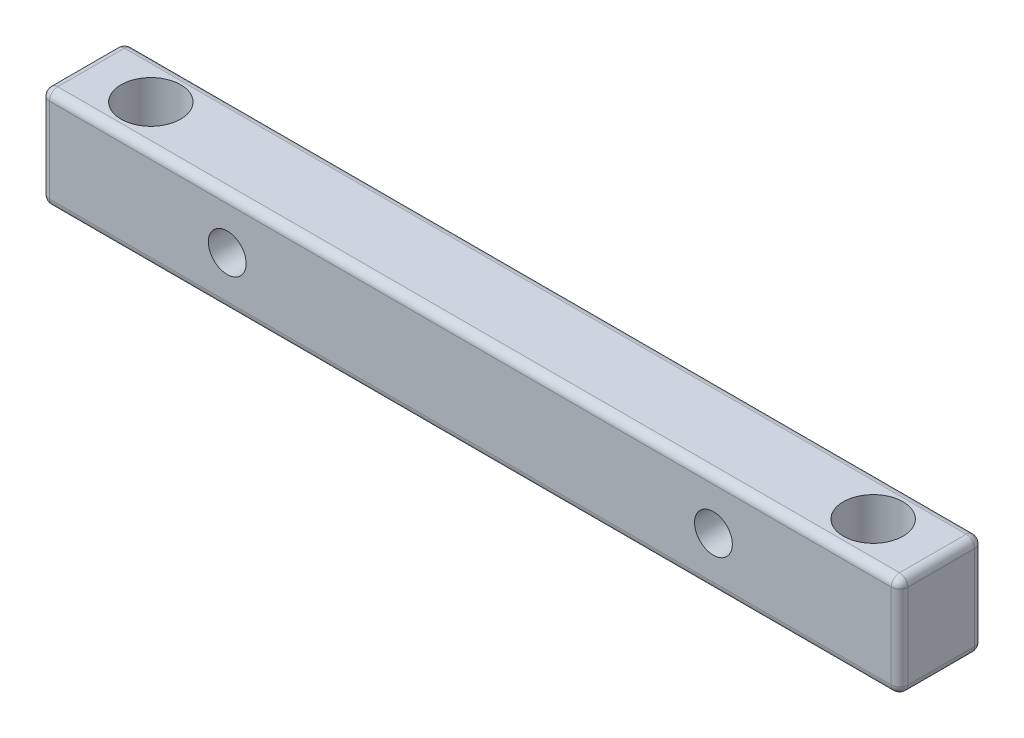
SolidWorks part; units mm, degrees
ref_plane "Front Plane" through (0, 0, 0) normal (0, 0, 1) x (1, 0, 0)
ref_plane "Top Plane" through (0, 0, 0) normal (0, 1, 0) x (1, 0, 0)
ref_plane "Right Plane" through (0, 0, 0) normal (1, 0, 0) x (0, 0, -1)
sketch "Sketch2" plane through (0, 0, 0) normal (0, 1, 0) x (1, 0, 0)
  line L0 (39.243, 7.62) -> (39.243, 0) construction
  line L1 (0, 7.62) -> (78.486, 7.62)
  line L2 (0, 7.62) -> (0, 0)
  line L3 (0, 0) -> (78.486, 0)
  line L4 (78.486, 7.62) -> (78.486, 0)
  line L5 (6.223, 3.81) -> (72.263, 3.81) construction
  circle A0 centre (6.223, 3.81) radius 2.7305
  circle A1 centre (72.263, 3.81) radius 2.7305
  point P10 (39.243, 3.81)
  dimension "D4" = 5.461
  dimension "D1" = 7.62
  dimension "D2" = 78.486
  dimension "D3" = 66.04
extrude "Boss-Extrude1" add sketch "Sketch2" along normal blind 9.271
sketch "Sketch3" plane through (0, 0, 0) normal (0, 0, 1) x (1, 0, 0)
  line L0 (39.243, 9.271) -> (39.243, 0) construction
  line L1 (17.018, 4.6355) -> (61.468, 4.6355) construction
  line L2 (0, 9.271) -> (78.486, 9.271) construction
  line L3 (0, 0) -> (78.486, 0) construction
  circle A0 centre (17.018, 4.6355) radius 1.7272
  circle A1 centre (61.468, 4.6355) radius 1.7272
  point P8 (39.243, 4.6355)
  dimension "D1" = 3.4544
  dimension "D2" = 44.45
extrude "Cut-Extrude1" cut sketch "Sketch3" against normal up to surface (7.62 mm away) up to face at (39.243, 4.6355, -7.62)
fillet "Fillet1" radius 0.762 12 edges at (0, 4.6355, -7.62) (0, 4.6355, 0) (0, 0, -3.81) (39.243, 0, -7.62) (39.243, 0, 0) (78.486, 0, -3.81) (78.486, 4.6355, -7.62) (78.486, 4.6355, 0) (78.486, 9.271, -3.81) (39.243, 9.271, -7.62) (0, 9.271, -3.81) (39.243, 9.271, 0)
